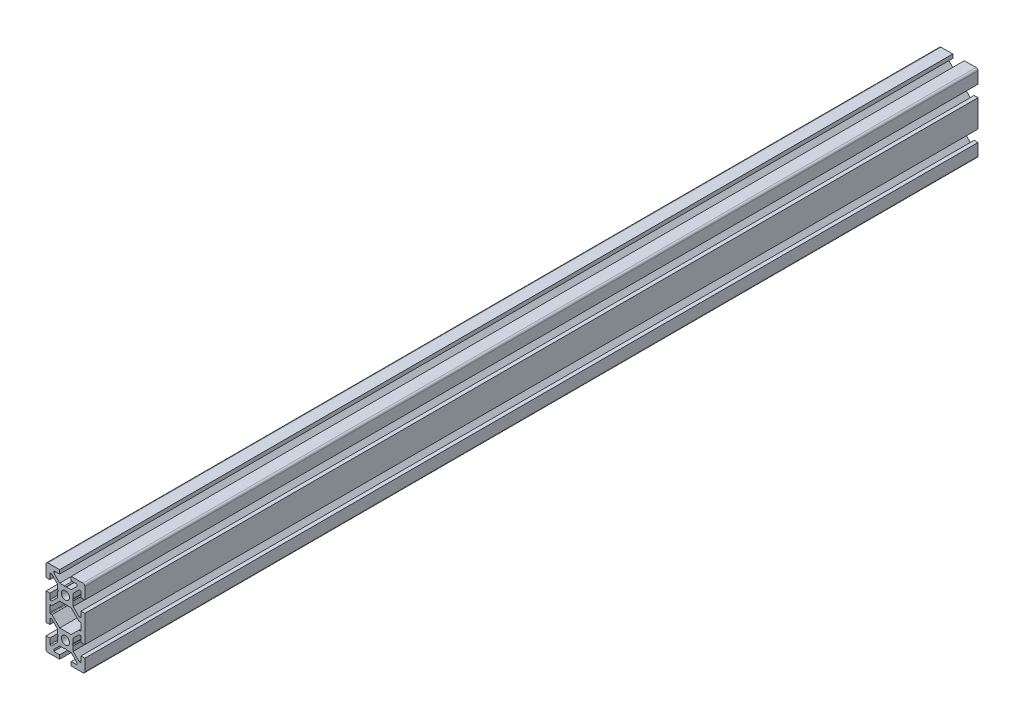
SolidWorks part; units mm, degrees
ref_plane "Front Plane" through (0, 0, 0) normal (0, 0, 1) x (1, 0, 0)
ref_plane "Top Plane" through (0, 0, 0) normal (0, 1, 0) x (1, 0, 0)
ref_plane "Right Plane" through (0, 0, 0) normal (1, 0, 0) x (0, 0, -1)
ref_plane "Plane1" through (0, 0, 0) normal (0, 0, 1) x (1, 0, 0)
sketch "Sketch1" plane through (0, 0, 0) normal (0, 0, 1) x (1, 0, 0)
  line L0 (-9, -20) -> (-3, -20)
  line L1 (-3, -20) -> (-3, -18)
  line L2 (-3, -18) -> (-6, -18)
  line L3 (-6, -18) -> (-6, -17.0607)
  line L4 (-6, -17.0607) -> (-2.9393, -14)
  line L5 (-2.9393, -14) -> (-0.5196, -14)
  line L6 (-0.5196, -14) -> (0, -13.7)
  line L7 (0, -13.7) -> (0.5196, -14)
  line L8 (0.5196, -14) -> (2.9393, -14)
  line L9 (2.9393, -14) -> (6, -17.0607)
  line L10 (6, -17.0607) -> (6, -18)
  line L11 (6, -18) -> (3, -18)
  line L12 (3, -18) -> (3, -20)
  line L13 (3, -20) -> (9, -20)
  line L14 (10, -19) -> (10, -13)
  line L15 (10, -13) -> (8, -13)
  line L16 (8, -13) -> (8, -16)
  line L17 (8, -16) -> (7.0607, -16)
  line L18 (7.0607, -16) -> (4, -12.9393)
  line L19 (4, -12.9393) -> (4, -10.5196)
  line L20 (4, -10.5196) -> (3.7, -10)
  line L21 (3.7, -10) -> (4, -9.4804)
  line L22 (4, -9.4804) -> (4, -7.0607)
  line L23 (4, -7.0607) -> (7.0607, -4)
  line L24 (7.0607, -4) -> (8, -4)
  line L25 (8, -4) -> (8, -7)
  line L26 (8, -7) -> (10, -7)
  line L27 (10, -7) -> (10, 7)
  line L28 (10, 7) -> (8, 7)
  line L29 (8, 7) -> (8, 4)
  line L30 (8, 4) -> (7.0607, 4)
  line L31 (7.0607, 4) -> (4, 7.0607)
  line L32 (4, 7.0607) -> (4, 9.4804)
  line L33 (4, 9.4804) -> (3.7, 10)
  line L34 (3.7, 10) -> (4, 10.5196)
  line L35 (4, 10.5196) -> (4, 12.9393)
  line L36 (4, 12.9393) -> (7.0607, 16)
  line L37 (7.0607, 16) -> (8, 16)
  line L38 (8, 16) -> (8, 13)
  line L39 (8, 13) -> (10, 13)
  line L40 (10, 13) -> (10, 19)
  line L41 (9, 20) -> (3, 20)
  line L42 (3, 20) -> (3, 18)
  line L43 (3, 18) -> (6, 18)
  line L44 (6, 18) -> (6, 17.0607)
  line L45 (6, 17.0607) -> (2.9393, 14)
  line L46 (2.9393, 14) -> (0.5196, 14)
  line L47 (0.5196, 14) -> (0, 13.7)
  line L48 (0, 13.7) -> (-0.5196, 14)
  line L49 (-0.5196, 14) -> (-2.9393, 14)
  line L50 (-2.9393, 14) -> (-6, 17.0607)
  line L51 (-6, 17.0607) -> (-6, 18)
  line L52 (-6, 18) -> (-3, 18)
  line L53 (-3, 18) -> (-3, 20)
  line L54 (-3, 20) -> (-9, 20)
  line L55 (-10, 19) -> (-10, 13)
  line L56 (-10, 13) -> (-8, 13)
  line L57 (-8, 13) -> (-8, 16)
  line L58 (-8, 16) -> (-7.0607, 16)
  line L59 (-7.0607, 16) -> (-4, 12.9393)
  line L60 (-4, 12.9393) -> (-4, 10.5196)
  line L61 (-4, 10.5196) -> (-3.7, 10)
  line L62 (-3.7, 10) -> (-4, 9.4804)
  line L63 (-4, 9.4804) -> (-4, 7.0607)
  line L64 (-4, 7.0607) -> (-7.0607, 4)
  line L65 (-7.0607, 4) -> (-8, 4)
  line L66 (-8, 4) -> (-8, 7)
  line L67 (-8, 7) -> (-10, 7)
  line L68 (-10, 7) -> (-10, -7)
  line L69 (-10, -7) -> (-8, -7)
  line L70 (-8, -7) -> (-8, -4)
  line L71 (-8, -4) -> (-7.0607, -4)
  line L72 (-7.0607, -4) -> (-4, -7.0607)
  line L73 (-4, -7.0607) -> (-4, -9.4804)
  line L74 (-4, -9.4804) -> (-3.7, -10)
  line L75 (-3.7, -10) -> (-4, -10.5196)
  line L76 (-4, -10.5196) -> (-4, -12.9393)
  line L77 (-4, -12.9393) -> (-7.0607, -16)
  line L78 (-7.0607, -16) -> (-8, -16)
  line L79 (-8, -16) -> (-8, -13)
  line L80 (-8, -13) -> (-10, -13)
  line L81 (-10, -13) -> (-10, -19)
  line L82 (-7.7, -2) -> (-7.0636, -2)
  line L83 (-6.8515, -2.0879) -> (-2.9393, -6)
  line L84 (-2.9393, -6) -> (2.9393, -6)
  line L85 (2.9393, -6) -> (6.8515, -2.0879)
  line L86 (7.0636, -2) -> (7.7, -2)
  line L87 (8, -1.7) -> (8, 1.7)
  line L88 (7.7, 2) -> (7.0636, 2)
  line L89 (6.8515, 2.0879) -> (2.9393, 6)
  line L90 (2.9393, 6) -> (-2.9393, 6)
  line L91 (-2.9393, 6) -> (-6.8515, 2.0879)
  line L92 (-7.0636, 2) -> (-7.7, 2)
  line L93 (-8, 1.7) -> (-8, -1.7)
  arc A0 (-10, -19) -> (-9, -20) centre (-9, -19) ccw
  arc A1 (9, -20) -> (10, -19) centre (9, -19) ccw
  arc A2 (10, 19) -> (9, 20) centre (9, 19) ccw
  arc A3 (-9, 20) -> (-10, 19) centre (-9, 19) ccw
  arc A4 (-8, -1.7) -> (-7.7, -2) centre (-7.7, -1.7) ccw
  arc A5 (-7.0636, -2) -> (-6.8515, -2.0879) centre (-7.0636, -2.3) cw
  arc A6 (6.8515, -2.0879) -> (7.0636, -2) centre (7.0636, -2.3) cw
  arc A7 (7.7, -2) -> (8, -1.7) centre (7.7, -1.7) ccw
  arc A8 (8, 1.7) -> (7.7, 2) centre (7.7, 1.7) ccw
  arc A9 (7.0636, 2) -> (6.8515, 2.0879) centre (7.0636, 2.3) cw
  arc A10 (-6.8515, 2.0879) -> (-7.0636, 2) centre (-7.0636, 2.3) cw
  arc A11 (-7.7, 2) -> (-8, 1.7) centre (-7.7, 1.7) ccw
extrude "Boss-Extrude1" add sketch "Sketch1" against normal blind 460
ref_plane "Plane2" through (0, 0, 0) normal (1, 0, 0) x (0, 0, -1)
sketch "Sketch2" plane through (0, 0, 0) normal (1, 0, 0) x (0, 0, -1)
  line L0 (0, 10) -> (0, 12.1)
  line L1 (0, 12.1) -> (460, 12.1)
  line L2 (460, 12.1) -> (460, 10)
  line L3 (460, 10) -> (0, 10)
  line L4 (460, 10) -> (0, 10) construction
revolve "Cut-Revolve1" cut sketch "Sketch2" angle 360 about L4
ref_plane "Plane3" through (0, 0, 0) normal (1, 0, 0) x (0, 0, -1)
sketch "Sketch3" plane through (0, 0, 0) normal (1, 0, 0) x (0, 0, -1)
  line L0 (0, -10) -> (0, -7.9)
  line L1 (0, -7.9) -> (460, -7.9)
  line L2 (460, -7.9) -> (460, -10)
  line L3 (460, -10) -> (0, -10)
  line L4 (460, -10) -> (0, -10) construction
revolve "Cut-Revolve2" cut sketch "Sketch3" angle 360 about L4
